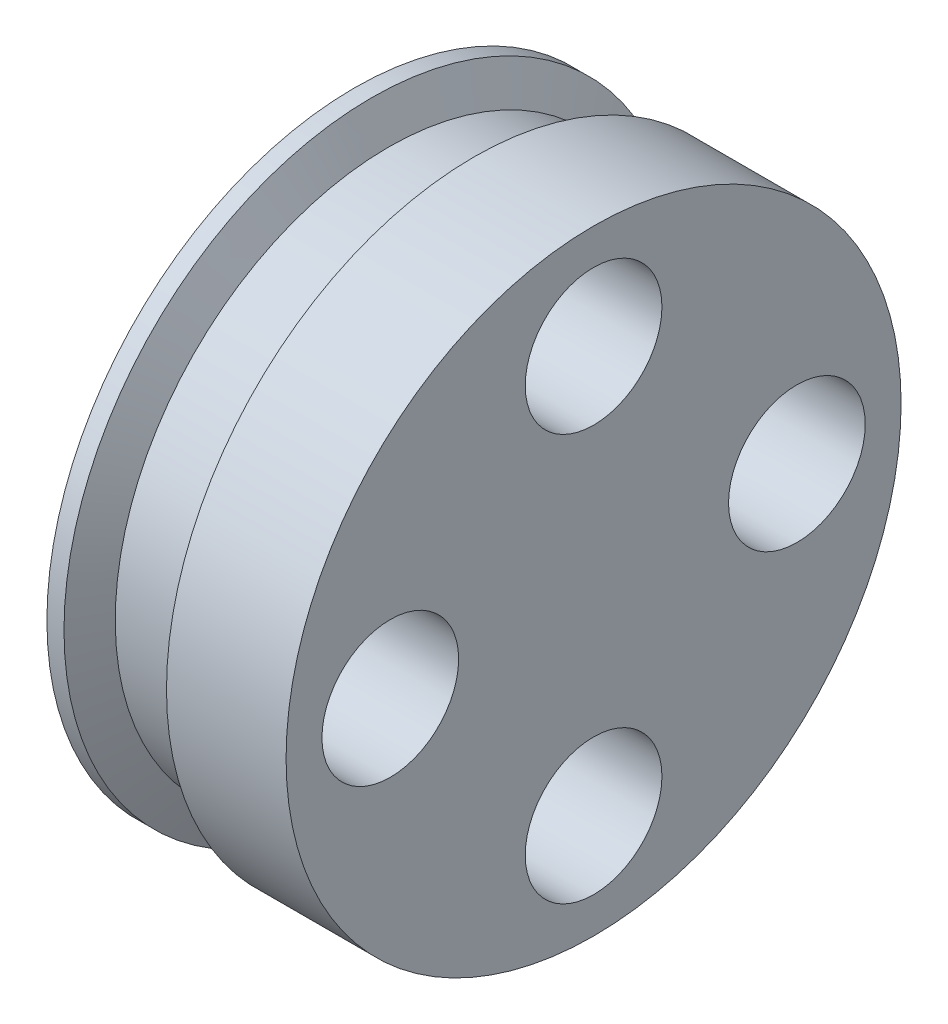
SolidWorks part; units mm, degrees
ref_plane "Plan de face" through (0, 0, 0) normal (0, 0, 1) x (1, 0, 0)
ref_plane "Plan de dessus" through (0, 0, 0) normal (0, 1, 0) x (1, 0, 0)
ref_plane "Plan de droite" through (0, 0, 0) normal (1, 0, 0) x (0, 0, -1)
sketch "Esquisse1" plane through (0, 0, 0) normal (0, 0, 1) x (1, 0, 0)
  line L0 (0, 0) -> (0, 9)
  line L1 (0, 9) -> (0.5, 9)
  line L2 (3.5, 9) -> (4, 9)
  line L4 (4, 0) -> (0, 0)
  line L5 (4, 0) -> (7, 0)
  line L6 (7, 0) -> (7, 9)
  line L7 (7, 9) -> (4, 9)
  line L8 (0.5, 9) -> (1, 8)
  line L9 (1, 8) -> (3, 8)
  line L10 (3, 8) -> (3.5, 9)
  dimension "D1" = 9
  dimension "D5" = 3
  dimension "D6" = 1
revolve "Révolution1" add sketch "Esquisse1" angle 360 about L4
sketch "Esquisse2" plane through (0, 0, 0) normal (-1, 0, 0) x (0, 0, 1)
  circle A0 centre (0, 5.95) radius 2
  circle A1 centre (5.95, 0) radius 2
  circle A2 centre (0, -5.95) radius 2
  circle A3 centre (-5.95, 0) radius 2
  point P12 (0, 0)
  dimension "D1" = 4
  dimension "D2" = 5.95
  dimension "D3" = 4
extrude "Enlèv. mat.-Extru.1" cut sketch "Esquisse2" against normal blind 10
